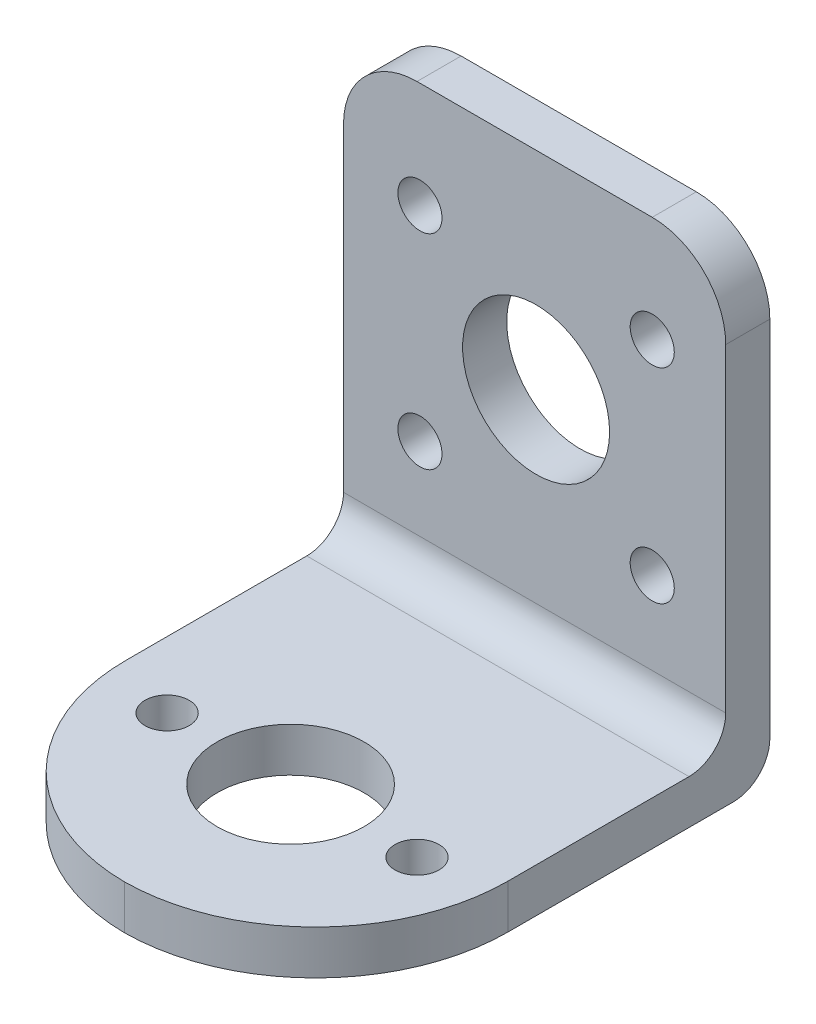
SolidWorks part; units mm, degrees
ref_plane "Front Plane" through (0, 0, 0) normal (0, 0, 1) x (1, 0, 0)
ref_plane "Top Plane" through (0, 0, 0) normal (0, 1, 0) x (1, 0, 0)
ref_plane "Right Plane" through (0, 0, 0) normal (1, 0, 0) x (0, 0, -1)
ref_plane "Plane1" through (0, -13.75, 0) normal (0, 1, 0) x (1, 0, 0)
sketch "Sketch1" plane through (0, -13.75, 0) normal (0, 1, 0) x (1, 0, 0)
  line L0 (13, -17.8) -> (13, 0)
  line L1 (13, 0) -> (-13, 0)
  line L2 (-13, 0) -> (-13, -17.8)
  arc A0 (-13, -17.8) -> (0, -30.8996) centre (0.1, -17.8) ccw
  arc A1 (0, -30.8996) -> (13, -17.8) centre (-0.1, -17.8) ccw
extrude "Boss-Extrude1" add sketch "Sketch1" against normal blind 3
sketch "Sketch2" plane through (0, -13.75, 0) normal (0, 1, 0) x (-1, 0, 0)
  line L0 (-13, 3) -> (13, 3)
  line L1 (13, 3) -> (13, 0)
  line L2 (13, 0) -> (-13, 0)
  line L3 (-13, 0) -> (-13, 3)
  dimension "D1" = 3
extrude "Boss-Extrude2" add sketch "Sketch2" along normal blind 29.2
hole_wizard "Ø10.0 (10) Diameter Hole1" positions "Sketch4" profile "Sketch3" hole size "Ø10.0" standard "ANSI Metric"
sketch "Sketch4" plane through (0, -13.75, 0) normal (0, 1, 0) x (1, 0, 0)
  point P0 (-0.1, -19.5)
sketch "Sketch3" plane through (-0.1, -13.75, 19.5) normal (1, 0, 0) x (0, 0, 1)
  line L0 (0, 0) -> (0, 3)
  line L1 (0, 3) -> (5, 3)
  line L2 (5, 3) -> (5, 0)
  line L5 (5, 0) -> (0, 0)
  line L11 (0, -6.35) -> (0, 107.95) construction
  dimension "Thru Hole Dia." = 10
  dimension "Thru Hole Depth" = 3
hole_wizard "Ø3.0 (3) Diameter Hole1" positions "Sketch6" profile "Sketch5" hole size "Ø3.0" standard "ANSI Metric" end condition through all
sketch "Sketch6" plane through (0, -13.75, 0) normal (0, 1, 0) x (1, 0, 0)
  line L0 (8.5, -19.5) -> (-8.5, -19.5)
  line L2 (0, -1.7) -> (0, -8.3107) construction
  point P0 (8.5, -19.5)
  point P1 (-8.5, -19.5)
  point P18 (0, -19.5)
  dimension "D1" = 17
sketch "Sketch5" plane through (8.5, -13.75, 19.5) normal (1, 0, 0) x (0, 0, 1)
  line L0 (0, 0) -> (0, 3)
  line L1 (0, 3) -> (1.5, 3)
  line L2 (1.5, 3) -> (1.5, 0)
  line L5 (1.5, 0) -> (0, 0)
  line L11 (0, -6.35) -> (0, 107.95) construction
  dimension "Thru Hole Dia." = 3
  dimension "Thru Hole Depth" = 3
hole_wizard "Ø10.0 (10) Diameter Hole2" positions "Sketch8" profile "Sketch7" hole size "Ø10.0" standard "ANSI Metric" end condition through all
sketch "Sketch8" plane through (0, 0, 3) normal (0, 0, 1) x (1, 0, 0)
  line L0 (-13, 15.45) -> (13, 15.45) construction
  point P0 (0.1, 1.35)
  point P2 (0, 0)
  dimension "D1" = 14.1
sketch "Sketch7" plane through (0.1, 1.35, 3) normal (1, 0, 0) x (0, -1, 0)
  line L0 (0, 0) -> (0, 3)
  line L1 (0, 3) -> (5, 3)
  line L2 (5, 3) -> (5, 0)
  line L5 (5, 0) -> (0, 0)
  line L11 (0, -6.35) -> (0, 107.95) construction
  dimension "Thru Hole Dia." = 10
  dimension "Thru Hole Depth" = 3
hole_wizard "Ø3.0 (3) Diameter Hole2" positions "Sketch10" profile "Sketch9" hole size "Ø3.0" standard "ANSI Metric" end condition through all
sketch "Sketch10" plane through (0, 0, 3) normal (0, 0, 1) x (1, 0, 0)
  line L0 (-13, 15.45) -> (13, 15.45) construction
  point P0 (-7.8, 8.25)
  point P1 (8, -5.65)
  point P2 (-7.8, -5.65)
  point P3 (8, 8.25)
  dimension "D1" = 7.2
  dimension "D2" = 7.2
  dimension "D3" = 21.1
  dimension "D4" = 21.1
sketch "Sketch9" plane through (-7.8, 8.25, 3) normal (1, 0, 0) x (0, -1, 0)
  line L0 (0, 0) -> (0, 3)
  line L1 (0, 3) -> (1.5, 3)
  line L2 (1.5, 3) -> (1.5, 0)
  line L5 (1.5, 0) -> (0, 0)
  line L11 (0, -6.35) -> (0, 107.95) construction
  dimension "Thru Hole Dia." = 3
  dimension "Thru Hole Depth" = 3
fillet "Fillet1" radius 2.5 2 edges at (0, -16.75, 0) (0, -13.75, 3)
fillet "Fillet3" radius 5 2 edges at (13, 15.45, 1.5) (-13, 15.45, 1.5)
